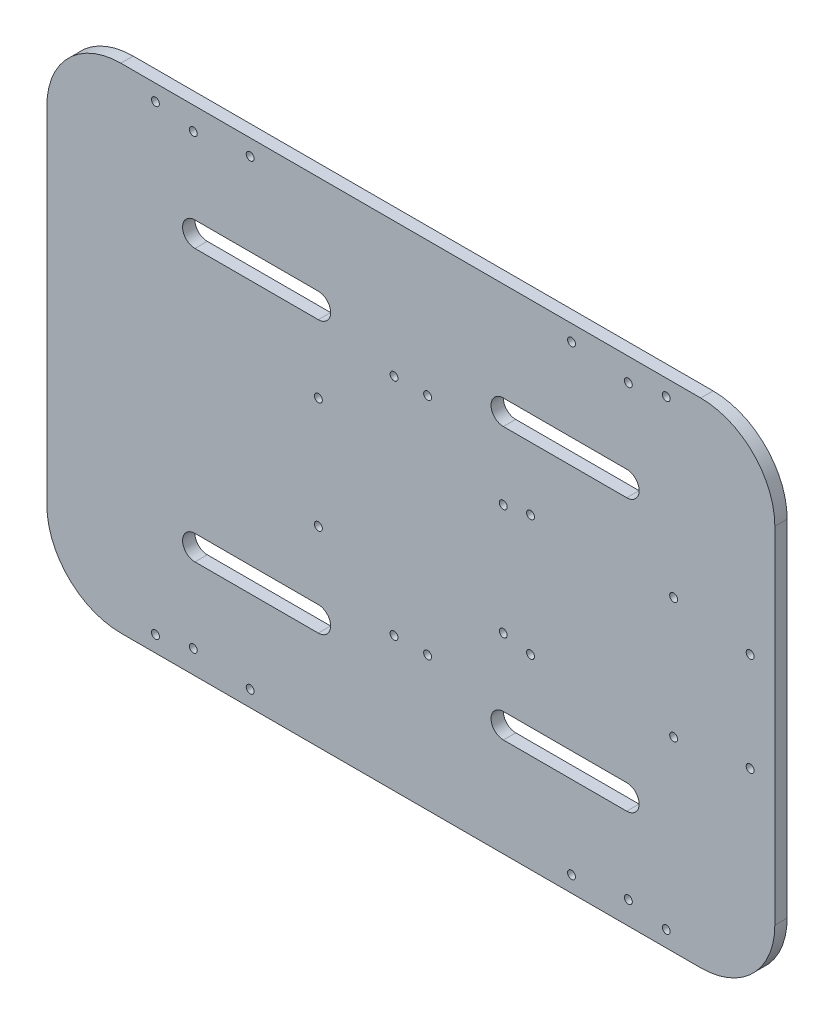
SolidWorks part; units mm, degrees
ref_plane "前视基准面" through (0, 0, 0) normal (0, 0, 1) x (1, 0, 0)
ref_plane "上视基准面" through (0, 0, 0) normal (0, 1, 0) x (1, 0, 0)
ref_plane "右视基准面" through (0, 0, 0) normal (1, 0, 0) x (0, 0, -1)
sketch "草图1" plane through (0, 0, 0) normal (0, 0, 1) x (1, 0, 0)
  line L0 (147.5, 200) -> (147.5, -59.0995) construction
  line L1 (0, 0) -> (295, 0)
  line L2 (0, 0) -> (0, 200)
  line L3 (0, 200) -> (295, 200)
  line L4 (295, 0) -> (295, 200)
  line L5 (0, 100) -> (372.4336, 100) construction
  dimension "D1" = 295
  dimension "D2" = 200
extrude "凸台-拉伸1" add sketch "草图1" along normal blind 5
sketch "草图2" plane through (0, 0, 5) normal (0, 0, 1) x (1, 0, 0)
  line L0 (0, 100) -> (316.1541, 100) construction
  line L1 (0, 200) -> (0, 0) construction
  line L2 (147.5, 200) -> (147.5, -26.6925) construction
  line L3 (295, 200) -> (0, 200) construction
  line L4 (295, 0) -> (295, 200) construction
  circle A0 centre (285, 120) radius 1.6
  circle A1 centre (285, 80) radius 1.6
  dimension "D1" = 3.2
  dimension "D2" = 10
  dimension "D3" = 20
extrude "寻迹传感器安装孔" cut sketch "草图2" against normal through all
sketch "草图3" plane through (0, 0, 5) normal (0, 0, 1) x (1, 0, 0)
  line L0 (295, 0) -> (295, 200) construction
  line L1 (0, 0) -> (295, 0) construction
  line L2 (147.5, 200) -> (147.5, 93.0025) construction
  line L3 (295, 200) -> (0, 200) construction
  line L4 (300, 100) -> (226.1544, 100) construction
  circle A0 centre (251, 6.5) radius 1.6
  circle A1 centre (212.6, 6.5) radius 1.6
  circle A2 centre (44, 6.5) radius 1.6
  circle A3 centre (82.4, 6.5) radius 1.6
  circle A4 centre (251, 193.5) radius 1.6
  circle A5 centre (212.6, 193.5) radius 1.6
  circle A6 centre (82.4, 193.5) radius 1.6
  circle A7 centre (44, 193.5) radius 1.6
  point P11 (147.5, 200)
  point P27 (263.0772, 100)
  dimension "D1" = 3.2
  dimension "D2" = 3.2
  dimension "D3" = 38.4
  dimension "D4" = 44
  dimension "D6" = 6.5
  dimension "D5" = 6.5
extrude "轮系安装孔" cut sketch "草图3" against normal blind 5
sketch "草图4" plane through (0, 0, 5) normal (0, 0, 1) x (1, 0, 0)
  line L0 (295, 100) -> (133.0651, 100) construction
  line L1 (295, 0) -> (295, 200) construction
  line L3 (196, 124.5) -> (254, 124.5) construction
  line L4 (196, 124.5) -> (196, 75.5) construction
  line L5 (196, 75.5) -> (254, 75.5) construction
  line L6 (254, 124.5) -> (254, 75.5) construction
  line L7 (196, 124.5) -> (254, 75.5) construction
  line L8 (196, 75.5) -> (254, 124.5) construction
  circle A3 centre (196, 124.5) radius 1.6
  circle A4 centre (254, 124.5) radius 1.6
  circle A5 centre (254, 75.5) radius 1.6
  circle A6 centre (196, 75.5) radius 1.6
  point P4 (225, 100)
  dimension "D1" = 3.2
  dimension "D2" = 58
  dimension "D3" = 49
  dimension "D4" = 70
extrude "树莓派安装孔" cut sketch "草图4" against normal blind 5
sketch "草图5" plane through (0, 0, 5) normal (0, 0, 1) x (1, 0, 0)
  line L0 (0, 100) -> (187.7042, 100) construction
  line L1 (0, 200) -> (0, 0) construction
  line L5 (110.04, 122.5) -> (184.96, 122.5) construction
  line L6 (110.04, 122.5) -> (110.04, 77.5) construction
  line L7 (110.04, 77.5) -> (184.96, 77.5) construction
  line L8 (184.96, 122.5) -> (184.96, 77.5) construction
  line L9 (110.04, 122.5) -> (184.96, 77.5) construction
  line L10 (110.04, 77.5) -> (184.96, 122.5) construction
  circle A2 centre (110.04, 122.5) radius 1.6
  circle A3 centre (184.96, 122.5) radius 1.6
  circle A4 centre (184.96, 77.5) radius 1.6
  circle A5 centre (110.04, 77.5) radius 1.6
  point P4 (147.5, 100)
  point P6 (148.7219, 74.6775)
  dimension "D1" = 3.2
  dimension "D4" = 147.5
  dimension "D2" = 74.92
  dimension "D3" = 45
extrude "电控板安装孔" cut sketch "草图5" against normal blind 5
sketch "草图8" plane through (0, 0, 5) normal (0, 0, 1) x (1, 0, 0)
  line L0 (0, 100) -> (295, 100) construction
  line L1 (0, 200) -> (0, 0) construction
  line L2 (295, 0) -> (295, 200) construction
  line L3 (147.5, 100) -> (147.5, 163.5495) construction
  line L4 (148.5092, 106.7526) -> (159.2249, 178.4534) construction
  circle A7 centre (154.2992, 145.4947) radius 1.6
  circle A8 centre (140.7008, 145.4947) radius 1.6
  circle A9 centre (154.2992, 54.5053) radius 1.6
  circle A10 centre (140.7008, 54.5053) radius 1.6
  point P14 (0, 0)
  point P16 (147.5, 100)
  dimension "D1" = 8.5
  dimension "D2" = 3.2
  dimension "D3" = 46
extrude "载物平台安装孔" cut sketch "草图8" against normal blind 50
sketch "草图10" plane through (0, 0, 5) normal (0, 0, 1) x (1, 0, 0)
  line L0 (0, 100) -> (295, 100) construction
  line L1 (0, 200) -> (0, 0) construction
  line L2 (295, 0) -> (295, 200) construction
  line L3 (147.5, 200) -> (147.5, 0) construction
  line L4 (295, 200) -> (0, 200) construction
  line L5 (0, 0) -> (295, 0) construction
  circle A0 centre (59.36, 190.7) radius 1.6
  circle A1 centre (235.64, 190.7) radius 1.6
  circle A2 centre (235.64, 9.3) radius 1.6
  circle A3 centre (59.36, 9.3) radius 1.6
  dimension "D1" = 3.2
  dimension "D2" = 9.3
  dimension "D3" = 59.36
extrude "弹簧安装孔" cut sketch "草图10" against normal through all
sketch "草图11" plane through (0, 0, 5) normal (0, 0, 1) x (1, 0, 0)
  line L0 (0, 100) -> (95.6567, 100) construction
  line L1 (0, 200) -> (0, 0) construction
  line L2 (60, 155) -> (110, 155) construction
  line L3 (60, 160) -> (110, 160)
  line L4 (60, 150) -> (110, 150)
  line L5 (60, 45) -> (110, 45) construction
  line L6 (60, 40) -> (110, 40)
  line L7 (60, 50) -> (110, 50)
  line L8 (147.5, 200) -> (147.5, -11.643) construction
  line L9 (235, 45) -> (185, 45) construction
  line L10 (295, 200) -> (0, 200) construction
  line L11 (235, 40) -> (185, 40)
  line L12 (235, 50) -> (185, 50)
  line L13 (235, 155) -> (185, 155) construction
  line L14 (235, 160) -> (185, 160)
  line L15 (235, 150) -> (185, 150)
  arc A0 (60, 160) -> (60, 150) centre (60, 155) ccw
  arc A1 (110, 150) -> (110, 160) centre (110, 155) ccw
  arc A2 (60, 40) -> (60, 50) centre (60, 45) cw
  arc A3 (110, 50) -> (110, 40) centre (110, 45) cw
  arc A4 (235, 40) -> (235, 50) centre (235, 45) ccw
  arc A5 (185, 50) -> (185, 40) centre (185, 45) ccw
  arc A6 (235, 160) -> (235, 150) centre (235, 155) cw
  arc A7 (185, 150) -> (185, 160) centre (185, 155) cw
  point P6 (85, 155)
  point P13 (85, 45)
  point P21 (147.5, 200)
  point P25 (210, 45)
  point P32 (210, 155)
  dimension "D2" = 50
  dimension "D3" = 60
  dimension "D1" = 10
  dimension "D4" = 50
extrude "走线" cut sketch "草图11" against normal blind 10
fillet "圆角1" radius 30 4 edges at (0, 0, 2.5) (295, 0, 2.5) (295, 200, 2.5) (0, 200, 2.5)
